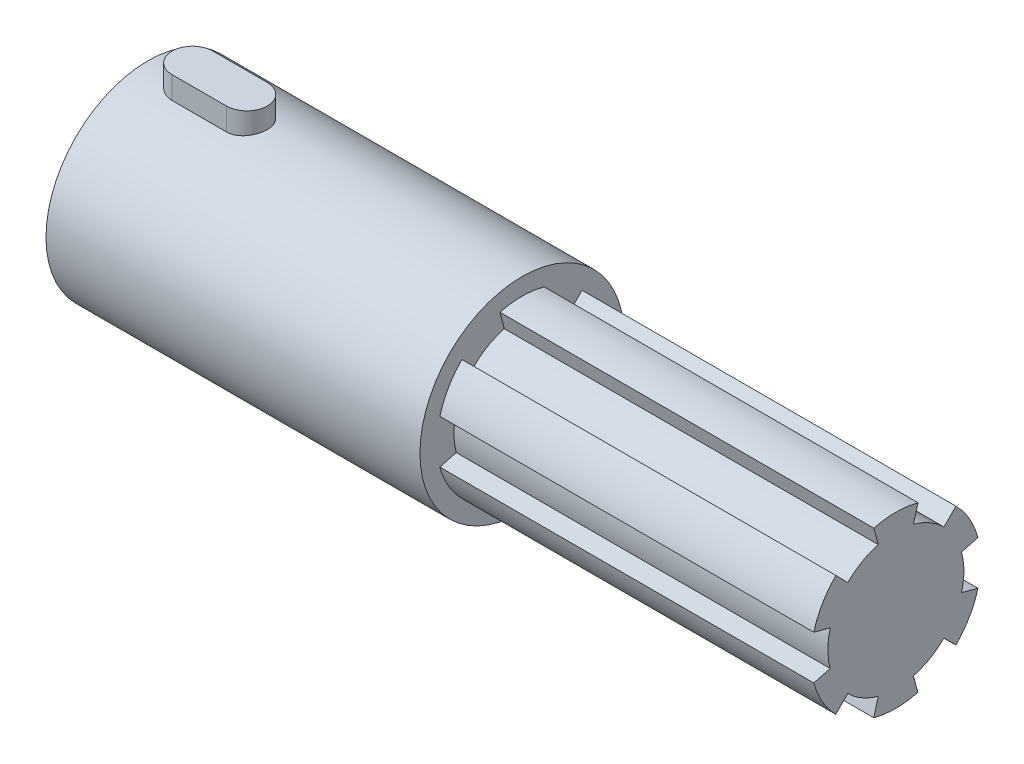
SolidWorks part; units mm, degrees
ref_plane "前视基准面" through (0, 0, 0) normal (0, 0, 1) x (1, 0, 0)
ref_plane "上视基准面" through (0, 0, 0) normal (0, 1, 0) x (1, 0, 0)
ref_plane "右视基准面" through (0, 0, 0) normal (1, 0, 0) x (0, 0, -1)
sketch "草图1" plane through (0, 0, 0) normal (1, 0, 0) x (0, 0, -1)
  circle A0 centre (0, 0) radius 15
extrude "凸台-拉伸1" add sketch "草图1" along normal blind 55
sketch "草图2" plane through (55, 0, 0) normal (1, 0, 0) x (0, 0, -1)
  line L0 (0, 0) -> (-3.2352, 12.0741) construction
  line L1 (0, 0) -> (3.2352, 12.0741) construction
  line L2 (-3.2352, 12.0741) -> (-2.5882, 9.6593)
  line L3 (3.2533, 12.0692) -> (2.5882, 9.6593)
  line L4 (8.8388, 8.8388) -> (7.0711, 7.0711)
  line L5 (12.0789, 3.2172) -> (9.6593, 2.5882)
  line L6 (12.0741, -3.2352) -> (9.6593, -2.5882)
  line L7 (8.8256, -8.852) -> (7.0711, -7.0711)
  line L8 (3.2352, -12.0741) -> (2.5882, -9.6593)
  line L9 (-3.2533, -12.0692) -> (-2.5882, -9.6593)
  line L10 (-8.8388, -8.8388) -> (-7.0711, -7.0711)
  line L11 (-12.0789, -3.2172) -> (-9.6593, -2.5882)
  line L12 (-12.0741, 3.2352) -> (-9.6593, 2.5882)
  line L13 (-8.8256, 8.852) -> (-7.0711, 7.0711)
  circle A0 centre (0, 0) radius 10
  arc A1 (8.8388, 8.8388) -> (12.0789, 3.2172) centre (0, 0) cw
  arc A2 (-3.2352, 12.0741) -> (3.2533, 12.0692) centre (0, 0) cw
  arc A3 (12.0741, -3.2352) -> (8.8256, -8.852) centre (0, 0) cw
  arc A4 (3.2352, -12.0741) -> (-3.2533, -12.0692) centre (0, 0) cw
  arc A5 (-8.8388, -8.8388) -> (-12.0789, -3.2172) centre (0, 0) cw
  arc A6 (-12.0741, 3.2352) -> (-8.8256, 8.852) centre (0, 0) cw
  dimension "D1" = 6
extrude "凸台-拉伸2" add sketch "草图2" along normal blind 55 contours A6 L12 A0 L13 | A0 | A2 L2 A0 L3 | A1 L4 A0 L5 | A3 L6 A0 L7 | A4 L8 A0 L9 | A5 L10 A0 L11
sketch "草图3" plane through (0, 0, 0) normal (-1, 0, 0) x (0, 0, 1)
  circle A0 centre (0, 0) radius 5
extrude "切除-拉伸1" cut sketch "草图3" against normal blind 25
sketch "草图4" plane through (0, 0, 0) normal (0, 1, 0) x (1, 0, 0)
  line L0 (-5.3212, 0) -> (60.5434, 0) construction
  line L1 (6.5453, 0) -> (14.5453, 0) construction
  line L2 (6.5453, 3) -> (14.5453, 3)
  line L3 (6.5453, -3) -> (14.5453, -3)
  arc A0 (6.5453, 3) -> (6.5453, -3) centre (6.5453, 0) ccw
  arc A1 (14.5453, -3) -> (14.5453, 3) centre (14.5453, 0) ccw
  point P5 (10.5453, 0)
  point P10 (0, 0)
extrude "凸台-拉伸3" add sketch "草图4" along normal blind 8 from offset 10
